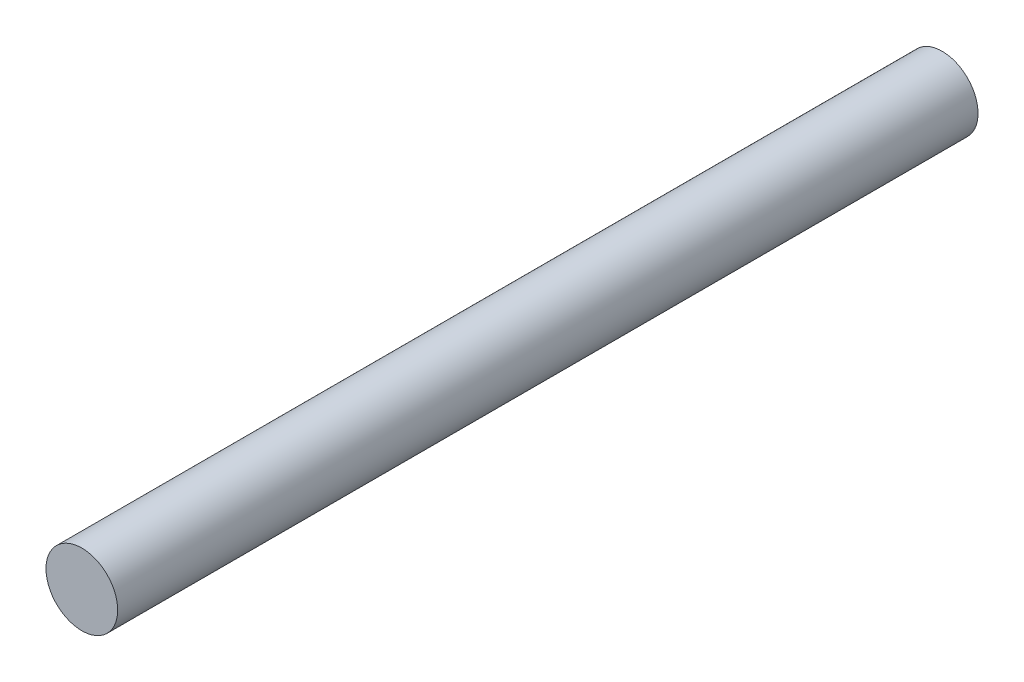
SolidWorks part; units mm, degrees
material "1023 Carbon Steel Sheet (SS)"
ref_plane "Front Plane" through (0, 0, 0) normal (0, 0, 1) x (1, 0, 0)
ref_plane "Top Plane" through (0, 0, 0) normal (0, 1, 0) x (1, 0, 0)
ref_plane "Right Plane" through (0, 0, 0) normal (1, 0, 0) x (0, 0, -1)
sketch "Sketch1" plane through (0, 0, 0) normal (0, 0, 1) x (1, 0, 0)
  circle A0 centre (0, 0) radius 1.5875
extrude "Boss-Extrude1" add sketch "Sketch1" along normal blind 38.1 contours A0
equation "\"PegDiam\"=0.125"
equation "\"D1@Sketch1\"=\"PegDiam\""
equation "\"PegLength\"=1.5"
equation "\"D1@Boss-Extrude1\"=\"PegLength\""
